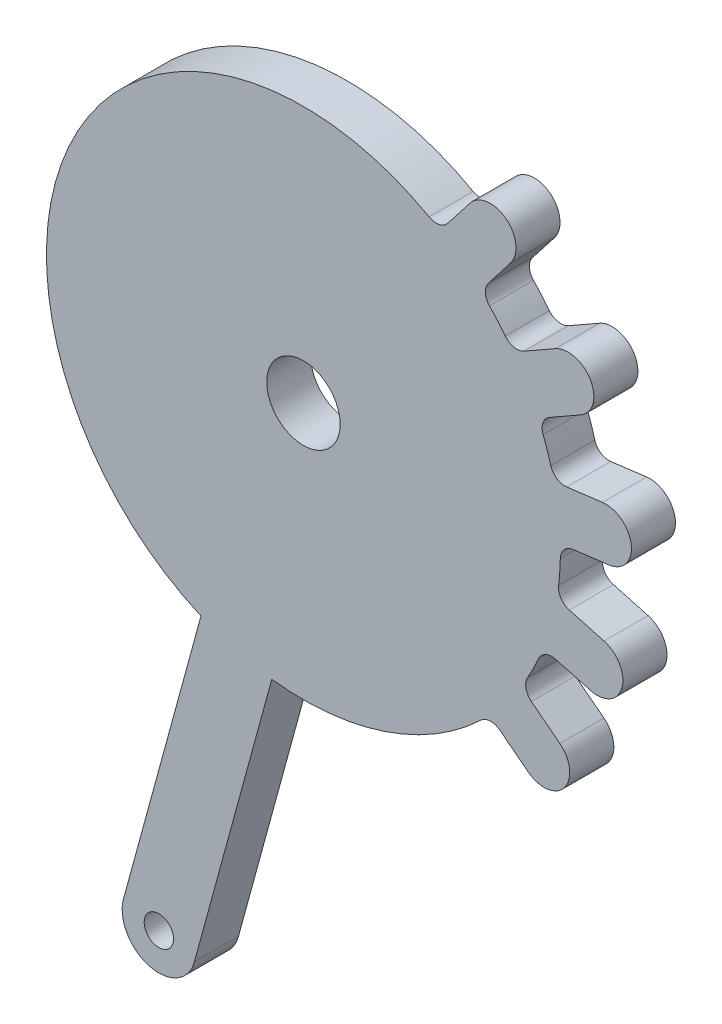
SolidWorks part; units mm, degrees
ref_plane "Front Plane" through (0, 0, 0) normal (0, 0, 1) x (1, 0, 0)
ref_plane "Top Plane" through (0, 0, 0) normal (0, 1, 0) x (1, 0, 0)
ref_plane "Right Plane" through (0, 0, 0) normal (1, 0, 0) x (0, 0, -1)
sketch "Sketch1" plane through (0, 0, 0) normal (0, 0, 1) x (1, 0, 0)
  line L0 (55.8028, -24.1777) -> (58.8694, -20.2285) construction
  line L1 (56.4139, -20.5374) -> (54.3668, -23.1737)
  line L2 (59.1783, -22.684) -> (57.1313, -25.3203)
  line L3 (63.9656, -29.2489) -> (61.0655, -30.9011)
  line L4 (62.233, -26.2078) -> (59.3329, -27.86)
  line L5 (65.8761, -37.146) -> (62.5645, -37.5627)
  line L6 (65.4392, -33.6734) -> (62.1276, -34.0901)
  line L7 (64.6192, -45.1732) -> (61.4002, -44.2908)
  line L8 (65.5444, -41.7977) -> (62.3255, -40.9154)
  line L9 (60.386, -52.1083) -> (57.7497, -50.0613)
  line L10 (62.5326, -49.3439) -> (59.8963, -47.2968)
  line L11 (38.0942, -54.0496) -> (32.824, -73.3427)
  line L12 (45.07, -38) -> (31.8819, -86.279) construction
  line L13 (42.9175, -55.3671) -> (37.6473, -74.6602)
  line L14 (32.824, -73.3427) -> (37.6473, -74.6602) construction
  circle A0 centre (45.07, -38) radius 2.5
  circle A1 centre (45.07, -38) radius 17.5
  circle A2 centre (45.07, -38) radius 22.5
  circle A3 centre (57.7961, -21.6107) radius 1.75
  circle A4 centre (63.0993, -27.7283) radius 1.75
  circle A5 centre (65.6577, -35.4097) radius 1.75
  circle A6 centre (65.0818, -43.4855) radius 1.75
  circle A7 centre (61.4593, -50.7261) radius 1.75
  arc A8 (32.824, -73.3427) -> (37.6473, -74.6602) centre (35.2267, -74.0344) ccw
  circle A9 centre (35.2267, -74.0344) radius 1
  point P39 (45.07, -38)
  point P44 (0, 0)
  dimension "D1" = 35
  dimension "D2" = 45
  dimension "D3" = 3.5
  dimension "D6" = 2
  dimension "D7" = 2.5002
  dimension "D5" = 5
  dimension "D8" = 20
  dimension "D4" = 5
extrude "Boss-Extrude1" add sketch "Sketch1" along normal blind 3 contours A1 A0 | A3 L1 A1 L2 | A3 | A4 | A4 L4 A1 L3 | A5 L6 A1 L5 | A5 | A6 L8 A1 L7 | A6 | A7 | A7 L10 A1 L9 | L11 A2 L13 A1 | L11 A8 L13 A2 A9
fillet "Fillet1" radius 1 10 edges at (59.8963, -47.2968, 1.5) (61.4002, -44.2908, 1.5) (62.3255, -40.9154, 1.5) (62.5645, -37.5627, 1.5) (62.1276, -34.0901, 1.5) (61.0655, -30.9011, 1.5) (59.3329, -27.86, 1.5) (57.1313, -25.3203, 1.5) (54.3668, -23.1737, 1.5) (57.7497, -50.0613, 1.5)
